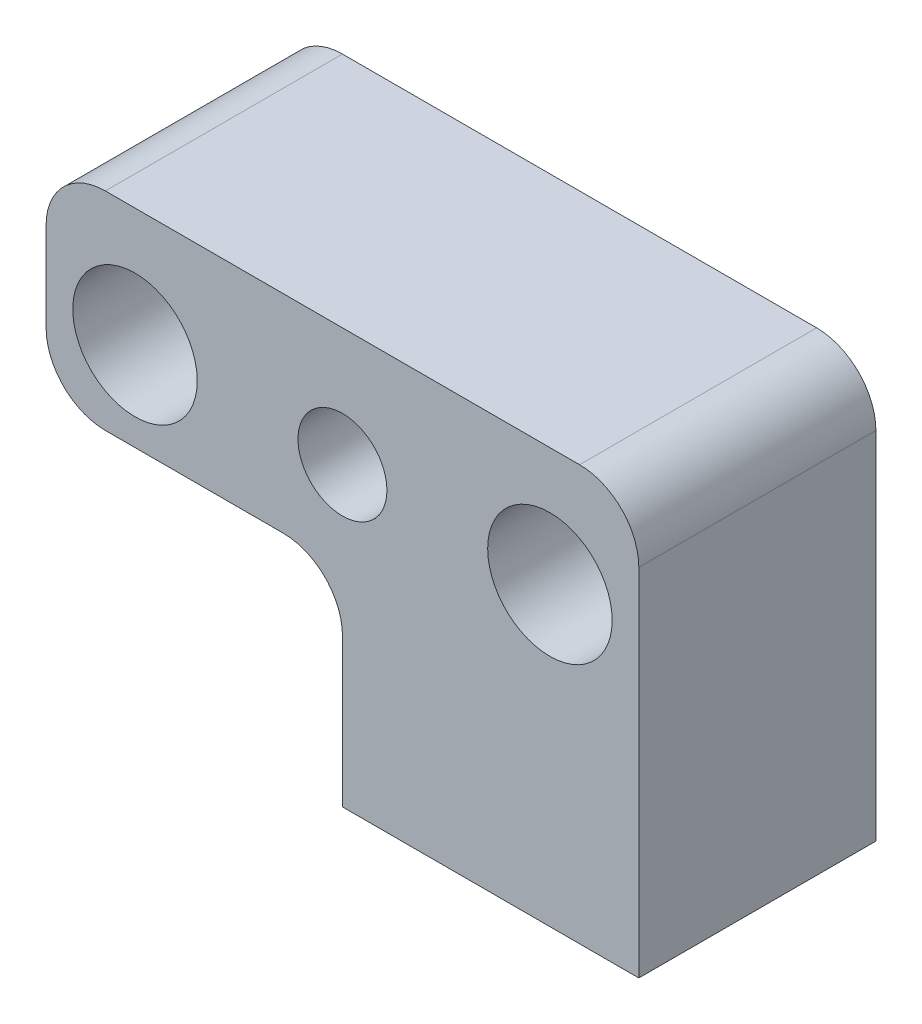
SolidWorks part; units mm, degrees
ref_plane "Front Plane" through (0, 0, 0) normal (0, 0, 1) x (1, 0, 0)
ref_plane "Top Plane" through (0, 0, 0) normal (0, 1, 0) x (1, 0, 0)
ref_plane "Right Plane" through (0, 0, 0) normal (1, 0, 0) x (0, 0, -1)
sketch "Sketch1" plane through (0, 0, 0) normal (0, 0, 1) x (1, 0, 0)
  line L1 (50, -40) -> (-50, -40)
  line L2 (50, -40) -> (50, 40)
  line L3 (50, 40) -> (-50, 40)
  line L4 (-50, -40) -> (-50, 40)
  line L5 (50, -40) -> (-50, 40) construction
  line L6 (50, 40) -> (-50, -40) construction
  point P0 (0, 0)
  dimension "D1" = 100
  dimension "D2" = 80
extrude "Boss-Extrude1" add sketch "Sketch1" along normal blind 40
sketch "Sketch2" plane through (0, 0, 40) normal (0, 0, 1) x (1, 0, 0)
  line L0 (-50, 0) -> (0, 0) construction
  line L1 (-50, 40) -> (-50, -40) construction
  line L2 (0, 0) -> (0, 40) construction
  line L3 (50, 40) -> (-50, 40) construction
  circle A0 centre (0, 0) radius 7.5
  circle A1 centre (-35, 0) radius 10.5
  circle A2 centre (35, 0) radius 10.5
  dimension "D1" = 21
  dimension "D3" = 15
  dimension "D2" = 15
extrude "Cut-Extrude1" cut sketch "Sketch2" against normal up to next
sketch "Sketch3" plane through (0, 0, 40) normal (0, 0, 1) x (1, 0, 0)
  line L0 (50, -40) -> (50, 40) construction
  line L1 (-50, 40) -> (50, 40)
  line L2 (-50, 40) -> (-50, 20)
  line L3 (-50, 20) -> (50, 20)
  line L4 (50, 40) -> (50, 20)
  dimension "D1" = 20
extrude "Cut-Extrude2" cut sketch "Sketch3" against normal up to next
sketch "Sketch4" plane through (0, -40, 0) normal (0, -1, 0) x (1, 0, 0)
  line L0 (-50, 20) -> (-38.6852, 20) construction
  line L1 (-50, 40) -> (-50, 0) construction
  line L2 (50, 40) -> (50, 0) construction
  line L3 (0, 0) -> (0, 40) construction
  line L4 (-50, 40) -> (50, 40) construction
  line L5 (-33.3148, 20) -> (-18.6852, 20) construction
  line L6 (-13.3148, 20) -> (50, 20) construction
  circle A2 centre (16, 20) radius 3
  circle A3 centre (36, 20) radius 3
  dimension "D3" = 6
  dimension "D4" = 6
  dimension "D1" = 34
  dimension "D2" = 14
extrude "Cut-Extrude3" cut sketch "Sketch4" against normal blind 25 and the other way blind 50
sketch "Sketch5" plane through (0, 0, 0) normal (0, 0, -1) x (-1, 0, 0)
  line L1 (50, -40) -> (0, -40)
  line L2 (50, -40) -> (50, -15)
  line L3 (50, -15) -> (0, -15)
  line L4 (0, -40) -> (0, -15)
  dimension "D1" = 50
  dimension "D2" = 25
extrude "Cut-Extrude4" cut sketch "Sketch5" against normal up to next
fillet "Fillet1" radius 10 1 edges at (0, -15, 20)
fillet "Fillet2" radius 10 1 edges at (-50, -15, 20)
fillet "Fillet3" radius 10 1 edges at (-50, 20, 20)
fillet "Fillet4" radius 10 1 edges at (50, 20, 20)
sketch "Sketch6" plane through (0, -40, 0) normal (0, -1, 0) x (1, 0, 0)
  line L0 (25, 40) -> (25, 0) construction
  line L1 (0, 40) -> (50, 40) construction
  line L2 (0, 0) -> (50, 0) construction
  line L8 (50, 0) -> (0, 40) construction
  line L9 (50, 40) -> (0, 0) construction
  line L10 (45, 5) -> (5, 5)
  line L11 (45, 5) -> (45, 35)
  line L12 (45, 35) -> (5, 35)
  line L13 (5, 5) -> (5, 35)
  line L14 (45, 5) -> (5, 35) construction
  line L15 (45, 35) -> (5, 5) construction
  line L16 (50, 0) -> (0, 0)
  line L17 (50, 0) -> (50, 40)
  line L18 (50, 40) -> (0, 40)
  line L19 (0, 0) -> (0, 40)
  line L20 (50, 0) -> (0, 40) construction
  line L21 (50, 40) -> (0, 0) construction
  point P6 (25, 20)
  point P12 (25, 20)
  point P17 (25, 20)
extrude "Boss-Extrude2" add sketch "Sketch6" along normal blind 10
